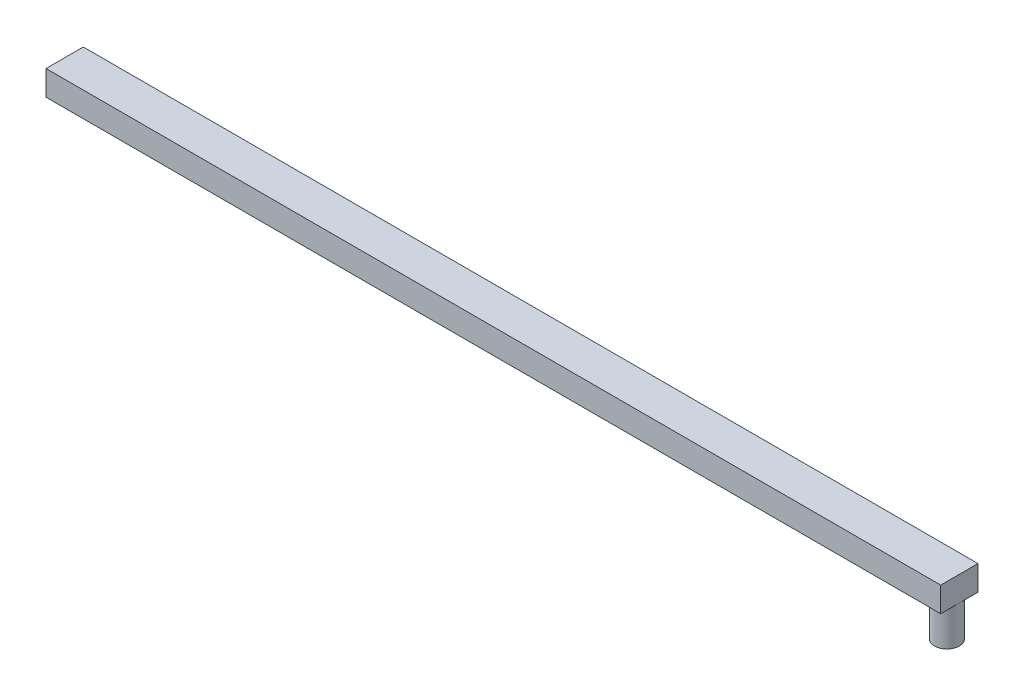
SolidWorks part; units mm, degrees
ref_plane "Front Plane" through (0, 0, 0) normal (0, 0, 1) x (1, 0, 0)
ref_plane "Top Plane" through (0, 0, 0) normal (0, 1, 0) x (1, 0, 0)
ref_plane "Right Plane" through (0, 0, 0) normal (1, 0, 0) x (0, 0, -1)
sketch "Sketch1" plane through (0, 0, 0) normal (0, 1, 0) x (1, 0, 0)
  circle A0 centre (0, 0) radius 1
  dimension "D1" = 2
extrude "Boss-Extrude1" add sketch "Sketch1" along normal blind 3
sketch "Sketch2" plane through (0, 3, 0) normal (0, 1, 0) x (1, 0, 0)
  line L1 (1, 1.5) -> (-71, 1.5)
  line L2 (1, 1.5) -> (1, -1.5)
  line L3 (1, -1.5) -> (-71, -1.5)
  line L4 (-71, 1.5) -> (-71, -1.5)
  circle A1 centre (0, 0) radius 1 construction
  point P4 (1, 0)
  dimension "D1" = 3
  dimension "D2" = 72
extrude "Boss-Extrude2" add sketch "Sketch2" along normal blind 2
sketch "Sketch3" plane through (0, 3, 0) normal (0, -1, 0) x (1, 0, 0)
  line L1 (-71, -1.5) -> (-71, 1.5) construction
  circle A0 centre (-70, 0) radius 0.5
  dimension "D1" = 1
  dimension "D2" = 1
extrude "Cut-Extrude6" cut sketch "Sketch3" against normal blind 1
equation "\"spiralD\"= 62"
equation "\"spiralHeight\"= 5"
equation "\"spiralHoleWidth\"=2"
equation "\"spiralED\"= 58"
equation "\"spiralHoleHeight\"=3"
equation "\"D1@Sketch1\"=\"spiralHoleWidth\""
equation "\"D1@Boss-Extrude1\"=\"spiralHoleHeight\""
equation "\"axisLength\"=10"
equation "\"D2@Sketch2\"=\"spiralD\" +10"
equation "\"D1@Sketch2\"=\"spiralHoleWidth\" +1"
equation "\"axisHeight\"=2"
equation "\"D1@Boss-Extrude2\"=\"axisHeight\""
equation "\"bitDepth\"=1"
equation "\"bitD\"=1"
equation "\"D1@Sketch3\"=\"bitD\""
equation "\"D2@Sketch3\"=\"bitD\"/2 +0.5"
equation "\"D1@Cut-Extrude6\"=\"bitDepth\""
